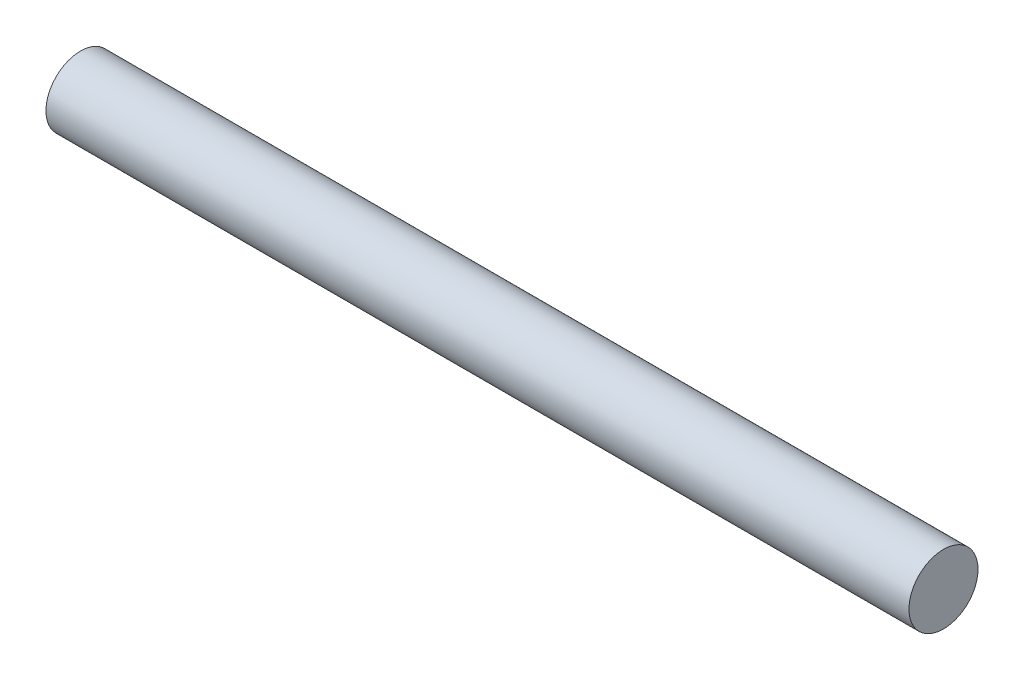
SolidWorks part; units mm, degrees
ref_plane "Спереди" through (0, 0, 0) normal (0, 0, 1) x (1, 0, 0)
ref_plane "Сверху" through (0, 0, 0) normal (0, 1, 0) x (1, 0, 0)
ref_plane "Справа" through (0, 0, 0) normal (1, 0, 0) x (0, 0, -1)
sketch "Эскиз1" plane through (0, 0, 0) normal (1, 0, 0) x (0, 0, -1)
  circle A0 centre (0, 0) radius 4
  dimension "D1" = 8
extrude "Вытянуть1" add sketch "Эскиз1" along normal blind 100
